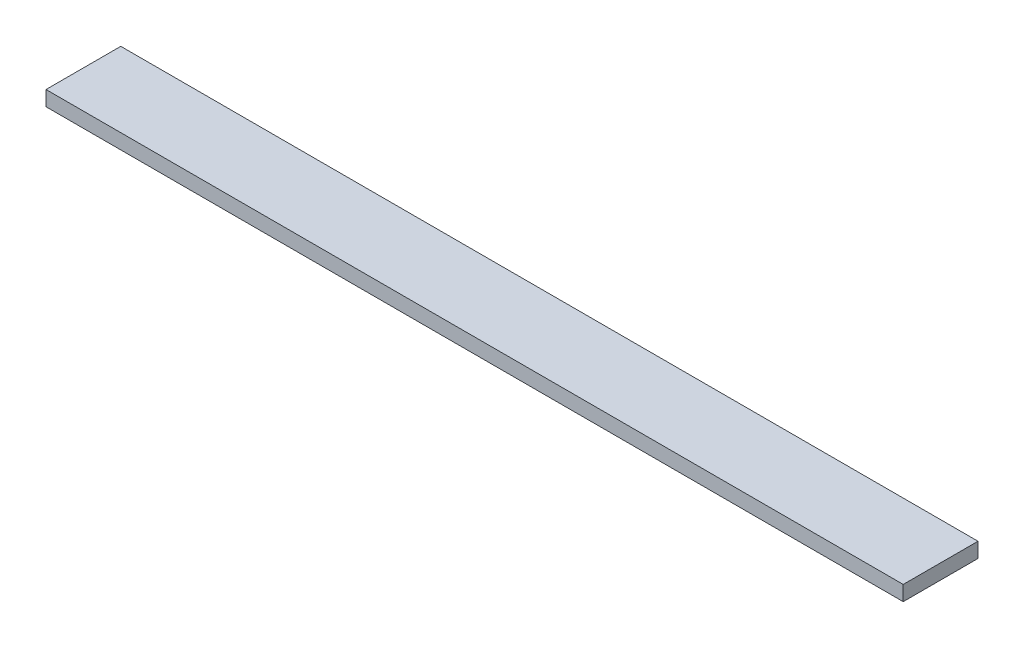
SolidWorks part; units mm, degrees
ref_plane "前视基准面" through (0, 0, 0) normal (0, 0, 1) x (1, 0, 0)
ref_plane "上视基准面" through (0, 0, 0) normal (0, 1, 0) x (1, 0, 0)
ref_plane "右视基准面" through (0, 0, 0) normal (1, 0, 0) x (0, 0, -1)
sketch "草图1" plane through (0, 0, 0) normal (0, 1, 0) x (1, 0, 0)
  line L1 (-37.1635, 12.7648) -> (77.4665, 12.7648)
  line L2 (-37.1635, 12.7648) -> (-37.1635, 2.7648)
  line L3 (-37.1635, 2.7648) -> (77.4665, 2.7648)
  line L4 (77.4665, 12.7648) -> (77.4665, 2.7648)
  dimension "D1" = 114.63
  dimension "D2" = 10
extrude "凸台-拉伸1" add sketch "草图1" along normal blind 2
